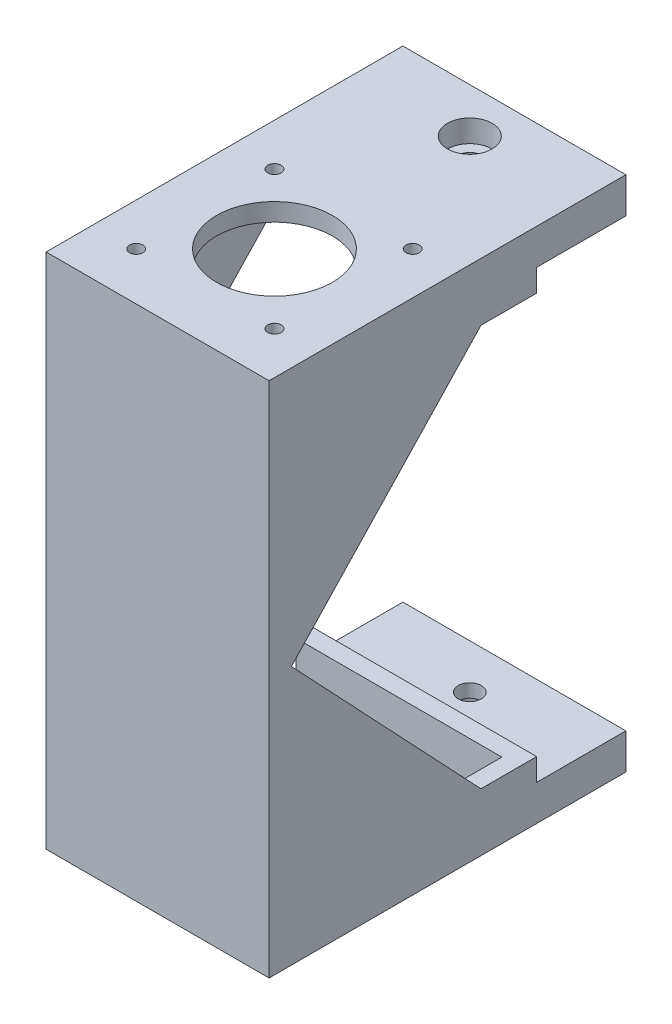
SolidWorks part; units mm, degrees
ref_plane "前视基准面" through (0, 0, 0) normal (0, 0, 1) x (1, 0, 0)
ref_plane "上视基准面" through (0, 0, 0) normal (0, 1, 0) x (1, 0, 0)
ref_plane "右视基准面" through (0, 0, 0) normal (1, 0, 0) x (0, 0, -1)
other "Configuration Table"
sketch "草图1" plane through (0, 0, 0) normal (0, 1, 0) x (1, 0, 0)
  line L1 (0, 0) -> (50, 0)
  line L2 (0, 0) -> (0, -20)
  line L3 (0, -20) -> (50, -20)
  line L4 (50, 0) -> (50, -20)
extrude "凸台-拉伸1" add sketch "草图1" along normal blind 8
sketch "草图2" plane through (0, 8, 0) normal (0, 1, 0) x (1, 0, 0)
  line L1 (0, 0) -> (50, 0)
  line L2 (0, 0) -> (0, 4)
  line L3 (0, 4) -> (50, 4)
  line L4 (50, 0) -> (50, 4)
  line L5 (0, -20) -> (50, -20)
  line L6 (0, -20) -> (0, -24)
  line L7 (0, -24) -> (50, -24)
  line L8 (50, -20) -> (50, -24)
extrude "凸台-拉伸2" add sketch "草图2" against normal blind 13 contours L2 L1 L4 L3 | L6 L5 L8 L7
sketch "草图3" plane through (0, 8, 0) normal (0, 1, 0) x (1, 0, 0)
  line L0 (0, -20) -> (0, -80)
  line L1 (0, 4) -> (0, -24) construction
  line L2 (0, -20) -> (50, -20)
  line L3 (50, -20) -> (50, -80)
  line L4 (0, -80) -> (50, -80)
extrude "凸台-拉伸3" add sketch "草图3" against normal blind 4
sketch "草图4" plane through (0, 4, 0) normal (0, -1, 0) x (1, 0, 0)
  line L0 (50, 80) -> (50, 24) construction
  line L1 (0, 80) -> (50, 80)
  line L2 (0, 80) -> (0, 75)
  line L3 (0, 75) -> (50, 75)
  line L4 (50, 80) -> (50, 75)
extrude "凸台-拉伸4" add sketch "草图4" along normal blind 40
sketch "草图6" plane through (0, 0, 0) normal (-1, 0, 0) x (0, 0, 1)
  line L0 (20, -100) -> (-4, -100)
  line L2 (75, -36) -> (80, -36)
  line L3 (20, -100) -> (20, -95)
  line L4 (20, -95) -> (24, -95)
  line L5 (24, -95) -> (24, -104)
  line L8 (75, -36) -> (75, -104)
  line L9 (80, -36) -> (80, -108)
  line L10 (80, -108) -> (-4, -108)
  line L11 (75, -104) -> (24, -104)
  line L12 (-4, -100) -> (-4, -108)
extrude "凸台-拉伸5" add sketch "草图6" against normal blind 50
sketch "草图7" plane through (0, 0, 0) normal (-1, 0, 0) x (0, 0, 1)
  line L1 (0, 0) -> (-4, 0)
  line L2 (0, 0) -> (0, -5)
  line L3 (0, -5) -> (-4, -5)
  line L4 (-4, 0) -> (-4, -5)
extrude "切除-拉伸1" cut sketch "草图7" against normal blind 50
sketch "草图8" plane through (0, 0, 0) normal (-1, 0, 0) x (0, 0, 1)
  line L1 (75, -104) -> (75, 4) construction
  line L2 (75, -50) -> (75, 4)
  line L3 (75, 4) -> (24, 4)
  line L4 (24, -5) -> (32.5, -5)
  line L5 (24, -5) -> (24, 4)
  line L6 (32.5, -5) -> (75, -50)
extrude "凸台-拉伸7" add sketch "草图8" against normal blind 3.8 contours L6 L2 L3 L5 L4
sketch "草图9" plane through (50, 0, 0) normal (1, 0, 0) x (0, 0, -1)
  line L0 (-24, 4) -> (-75, 4)
  line L1 (-75, 4) -> (-75, -50)
  line L2 (-75, -104) -> (-75, 4) construction
  line L3 (-75, -50) -> (-32.5, -5)
  line L4 (-32.5, -5) -> (-24, -5)
  line L5 (-24, -5) -> (-24, 4)
  line L7 (-24, -104) -> (-75, -104)
  line L8 (-75, -104) -> (-75, -50)
  line L9 (-24, -95) -> (-24, -104)
  line L10 (-24, -95) -> (-32.5, -95)
  line L11 (-32.5, -95) -> (-75, -50)
  line M16 (-24, -95) -> (-24, -104)
  line M17 (-24, -104) -> (-75, -104)
  line M18 (-75, -104) -> (-75, 4)
  line M19 (-75, 4) -> (-24, 4)
  line M20 (-24, 4) -> (-24, -5)
extrude "凸台-拉伸8" add sketch "草图9" against normal blind 3.8 contours L3 L4 M20 M19 M18 | L10 L11 M18 M17 M16
sketch "草图11" plane through (0, 4, 0) normal (0, -1, 0) x (-1, 0, 0)
  line L1 (-46.2, -75) -> (-3.8, -75)
  line L2 (-46.2, -75) -> (-46.2, -32.6)
  line L3 (-46.2, -32.6) -> (-3.8, -32.6)
  line L4 (-3.8, -75) -> (-3.8, -32.6)
  circle A0 centre (-40.5, -38.3) radius 1.5
  circle A1 centre (-9.5, -38.3) radius 1.5
  circle A2 centre (-40.5, -69.3) radius 1.5
  circle A3 centre (-9.5, -69.3) radius 1.5
  circle A4 centre (-25, -53.8) radius 13
extrude "切除-拉伸2" cut sketch "草图11" against normal blind 4 contours A0 | A1 | A3 | A4 | A2
sketch "草图14" plane through (0, 0, 0) normal (-1, 0, 0) x (0, 0, 1)
  line L1 (20, -100) -> (-4, -100) construction
  line L2 (0, -100) -> (0, -95)
  line L3 (0, -95) -> (-4, -95)
  line L4 (-4, -100) -> (-4, -95)
  line L5 (-4, -100) -> (0, -100)
  line L6 (0, 0) -> (0, -5)
  line L7 (0, -5) -> (-4, -5)
  line L8 (-4, -5) -> (-4, 0)
  line L9 (-4, 0) -> (0, 0)
extrude "凸台-拉伸9" add sketch "草图14" against normal blind 50
sketch "草图15" plane through (0, 0, 0) normal (0, -1, 0) x (1, 0, 0)
  line L0 (0, 20) -> (50, 0)
  circle A0 centre (25, 10) radius 2.6
extrude "切除-拉伸3" cut sketch "草图15" against normal blind 50 contours L0 A0 | L0 A0
sketch "草图16" plane through (0, 8, 0) normal (0, 1, 0) x (1, 0, 0)
  circle A0 centre (25, -10) radius 2.6
extrude "切除-拉伸4" cut sketch "草图16" against normal blind 200
sketch "草图17" plane through (0, 8, 0) normal (0, 1, 0) x (1, 0, 0)
  circle A0 centre (25, -10) radius 5
extrude "切除-拉伸5" cut sketch "草图17" against normal blind 5
sketch "草图18" plane through (0, -108, 0) normal (0, -1, 0) x (1, 0, 0)
  circle A0 centre (25, 10) radius 5
extrude "切除-拉伸6" cut sketch "草图18" against normal blind 5
sketch "草图19" plane through (0, -5, 0) normal (0, -1, 0) x (-1, 0, 0)
  line L1 (0, 0) -> (-50, 0)
  line L2 (0, 0) -> (0, 4)
  line L3 (0, 4) -> (-50, 4)
  line L4 (-50, 0) -> (-50, 4)
extrude "切除-拉伸7" cut sketch "草图19" against normal blind 20
sketch "草图20" plane through (0, -95, 0) normal (0, 1, 0) x (1, 0, 0)
  line L1 (0, 0) -> (50, 0)
  line L2 (0, 0) -> (0, 4)
  line L3 (0, 4) -> (50, 4)
  line L4 (50, 0) -> (50, 4)
extrude "切除-拉伸8" cut sketch "草图20" against normal blind 20
